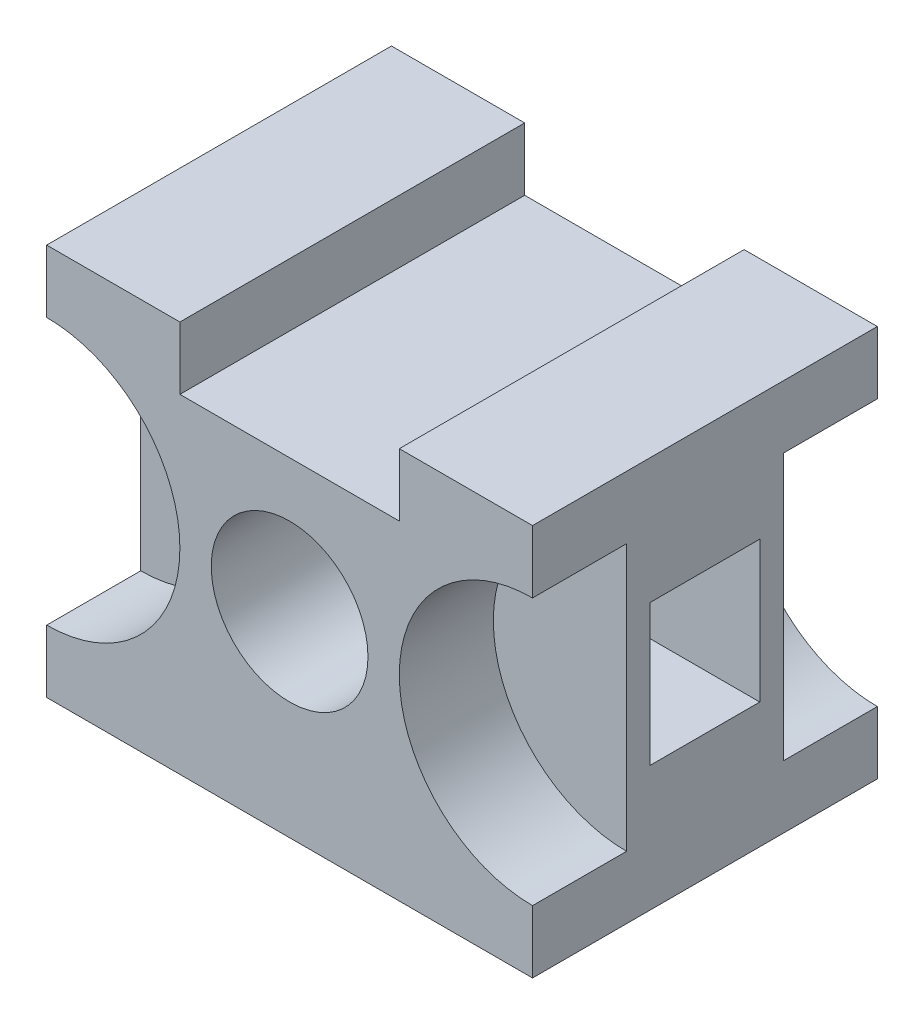
SolidWorks part; units mm, degrees
ref_plane "Front Plane" through (0, 0, 0) normal (0, 0, 1) x (1, 0, 0)
ref_plane "Top Plane" through (0, 0, 0) normal (0, 1, 0) x (1, 0, 0)
ref_plane "Right Plane" through (0, 0, 0) normal (1, 0, 0) x (0, 0, -1)
sketch "Sketch1" plane through (0, 0, 0) normal (0, 0, 1) x (1, 0, 0)
  line L1 (0, 0) -> (62, 0)
  line L2 (0, 0) -> (0, 50)
  line L3 (0, 50) -> (62, 50)
  line L4 (62, 0) -> (62, 50)
  dimension "D1" = 62
  dimension "D2" = 50
extrude "Boss-Extrude1" add sketch "Sketch1" against normal blind 44
sketch "Sketch2" plane through (0, 0, 0) normal (0, 0, 1) x (1, 0, 0)
  line L4 (0, 50) -> (0, 0)
  line L5 (0, 0) -> (62, 0)
  line L6 (62, 0) -> (62, 50)
  line L7 (62, 50) -> (0, 50)
  line L8 (0, 50) -> (0, 0)
  line L9 (0, 0) -> (62, 0)
  line L10 (62, 0) -> (62, 50)
  line L11 (62, 50) -> (0, 50)
  circle A0 centre (31, 25) radius 10
  point P6 (30.801, 25.8622)
  dimension "D2" = 20
  dimension "D3" = 31
  dimension "D4" = 25
  dimension "D1" = 0
extrude "Cut-Extrude1" cut sketch "Sketch2" against normal blind 56 contours A0
sketch "Sketch3" plane through (0, 0, 0) normal (0, 0, 1) x (1, 0, 0)
  line L4 (0, 50) -> (0, 0)
  line L5 (0, 0) -> (62, 0)
  line L6 (62, 0) -> (62, 50)
  line L7 (62, 50) -> (0, 50)
  line L8 (0, 50) -> (0, 0)
  line L9 (0, 0) -> (62, 0)
  line L10 (62, 0) -> (62, 50)
  line L11 (62, 50) -> (0, 50)
  circle A0 centre (0, 25) radius 17
  circle A1 centre (62, 25) radius 17
  dimension "D2" = 34
  dimension "D3" = 34
  dimension "D1" = 0
extrude "Cut-Extrude2" cut sketch "Sketch3" against normal blind 12 contours L8 A0 | L10 A1
sketch "Sketch4" plane through (0, 0, -44) normal (0, 0, -1) x (-1, 0, 0)
  line L4 (0, 0) -> (0, 50)
  line L5 (0, 50) -> (-62, 50)
  line L6 (-62, 50) -> (-62, 0)
  line L7 (-62, 0) -> (0, 0)
  line L8 (0, 0) -> (0, 50)
  line L9 (0, 50) -> (-62, 50)
  line L10 (-62, 50) -> (-62, 0)
  line L11 (-62, 0) -> (0, 0)
  circle A0 centre (-62, 25) radius 17
  circle A1 centre (0, 25) radius 17
  dimension "D2" = 34
  dimension "D3" = 34
  dimension "D1" = 0
extrude "Cut-Extrude3" cut sketch "Sketch4" against normal blind 12 contours L10 A0 | L8 A1
sketch "Sketch5" plane through (0, 0, 0) normal (0, 0, 1) x (1, 0, 0)
  line L1 (17, 50) -> (45, 50)
  line L2 (17, 50) -> (17, 42)
  line L3 (17, 42) -> (45, 42)
  line L4 (45, 50) -> (45, 42)
  line L6 (0, 50) -> (0, 42)
  line L7 (0, 8) -> (0, 0)
  line L8 (0, 0) -> (62, 0)
  line L9 (62, 0) -> (62, 8)
  line L10 (62, 42) -> (62, 50)
  line L11 (62, 50) -> (0, 50)
  line L12 (0, 50) -> (0, 42)
  line L13 (0, 8) -> (0, 0)
  line L14 (0, 0) -> (62, 0)
  line L15 (62, 0) -> (62, 8)
  line L16 (62, 42) -> (62, 50)
  line L17 (62, 50) -> (0, 50)
  arc A2 (0, 8) -> (0, 42) centre (0, 25) ccw
  arc A3 (62, 42) -> (62, 8) centre (62, 25) ccw
  arc A4 (0, 8) -> (0, 42) centre (0, 25) ccw
  arc A5 (62, 42) -> (62, 8) centre (62, 25) ccw
  line M20 (62, 50) -> (0, 50)
  dimension "D2" = 8
  dimension "D3" = 28
  dimension "D4" = 17
  dimension "D1" = 0
extrude "Cut-Extrude4" cut sketch "Sketch5" against normal blind 71 contours L4 L2 L3 M20
sketch "Sketch6" plane through (0, 0, 0) normal (-1, 0, 0) x (0, 0, 1)
  line L1 (-29, 34) -> (-15, 34)
  line L2 (-29, 34) -> (-29, 16)
  line L3 (-29, 16) -> (-15, 16)
  line L4 (-15, 34) -> (-15, 16)
  line L12 (-44, 42) -> (-32, 42)
  line L13 (-32, 42) -> (-32, 8)
  line L14 (-32, 8) -> (-44, 8)
  line L15 (-44, 8) -> (-44, 0)
  line L16 (-44, 0) -> (0, 0)
  line L17 (0, 0) -> (0, 8)
  line L18 (0, 8) -> (-12, 8)
  line L19 (-12, 8) -> (-12, 42)
  line L20 (-12, 42) -> (0, 42)
  line L21 (0, 42) -> (0, 50)
  line L22 (0, 50) -> (-44, 50)
  line L23 (-44, 50) -> (-44, 42)
  line L24 (-44, 42) -> (-32, 42)
  line L25 (-32, 42) -> (-32, 8)
  line L26 (-32, 8) -> (-44, 8)
  line L27 (-44, 8) -> (-44, 0)
  line L28 (-44, 0) -> (0, 0)
  line L29 (0, 0) -> (0, 8)
  line L30 (0, 8) -> (-12, 8)
  line L31 (-12, 8) -> (-12, 42)
  line L32 (-12, 42) -> (0, 42)
  line L33 (0, 42) -> (0, 50)
  line L34 (0, 50) -> (-44, 50)
  line L35 (-44, 50) -> (-44, 42)
  dimension "D2" = 14
  dimension "D3" = 18
  dimension "D4" = 3
  dimension "D5" = 16
  dimension "D1" = 0
extrude "Cut-Extrude5" cut sketch "Sketch6" against normal blind 71 contours L2 L1 L4 L3
